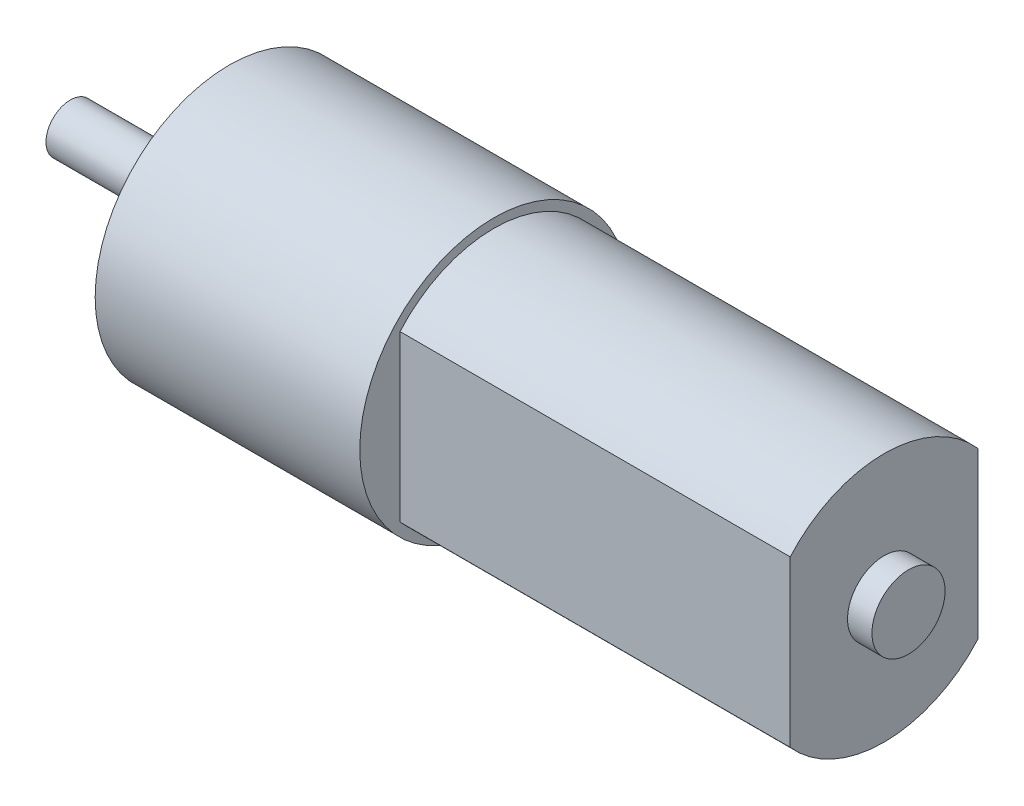
SolidWorks part; units mm, degrees
ref_plane "Plan de face" through (0, 0, 0) normal (0, 0, 1) x (1, 0, 0)
ref_plane "Plan de dessus" through (0, 0, 0) normal (0, 1, 0) x (1, 0, 0)
ref_plane "Plan de droite" through (0, 0, 0) normal (1, 0, 0) x (0, 0, -1)
sketch "Esquisse1" plane through (0, 0, 0) normal (0, 0, 1) x (1, 0, 0)
  line L0 (38.7034, 0) -> (-58.2382, 0) construction
  line L1 (-13.0357, 0) -> (-13.0357, -2)
  line L2 (-13.0357, -2) -> (-3, -2)
  line L3 (-3, -2) -> (-3, -4)
  line L4 (-3, -4) -> (-2, -4)
  line L5 (-2, -4) -> (-2, -7)
  line L6 (-2, -7) -> (0, -7)
  line L7 (0, -7) -> (0, -11)
  line L8 (0, -11) -> (21.7, -11)
  line L9 (21.7, -11) -> (21.7, -10.25)
  line L10 (21.7, -10.25) -> (53.7, -10.25)
  line L11 (53.7, -10.25) -> (53.7, -3)
  line L12 (53.7, -3) -> (55.7, -3)
  line L13 (55.7, -3) -> (55.7, 0)
  line L14 (55.7, 0) -> (-13.0357, 0)
  point P16 (0, -9)
  dimension "D1" = 2
  dimension "D2" = 11.0357
  dimension "D3" = 2
  dimension "D4" = 21.7
  dimension "D5" = 32
  dimension "D6" = 3
  dimension "D7" = 2
  dimension "D8" = 10.25
  dimension "D9" = 11
  dimension "D10" = 7
  dimension "D11" = 4
  dimension "D12" = 1
revolve "Révolution1" add sketch "Esquisse1" angle 360 about L0
sketch "Esquisse2" plane through (53.7, 0, 0) normal (1, 0, 0) x (0, 0, -1)
  line L0 (0, 0) -> (0, -12.8806) construction
  line L1 (-7.7, 11.1958) -> (-7.7, -12.176)
  line L2 (7.7, -12.176) -> (7.7, 11.1958)
  line L3 (-7.7, 11.1958) -> (-16.0203, 11.1958)
  line L4 (-16.0203, 11.1958) -> (-16.0203, -12.176)
  line L5 (-16.0203, -12.176) -> (-7.7, -12.176)
  line L6 (7.7, -12.176) -> (15.6221, -12.176)
  line L7 (15.6221, -12.176) -> (15.6221, 11.1958)
  line L8 (15.6221, 11.1958) -> (7.7, 11.1958)
  dimension "D1" = 15.4
extrude "Enlèv. mat.-Extru.1" cut sketch "Esquisse2" against normal up to surface (32 mm away) up to face at (21.7, 0, -10.25)
sketch "Esquisse3" plane through (-2, 0, 0) normal (-1, 0, 0) x (0, 0, 1)
  line L0 (6.7922, 1.6931) -> (1.6931, 6.7922)
  line L1 (0, 0) -> (-12.3198, 12.3198) construction
  line L2 (-6.7922, -1.6931) -> (-1.6931, -6.7922)
  line L3 (0, 15.4295) -> (0, 0) construction
  circle A0 centre (0, 0) radius 7 construction
  circle A1 centre (0, 0) radius 7 construction
  arc A2 (-6.7922, -1.6931) -> (-1.6931, -6.7922) centre (0, 0) ccw
  arc A3 (1.6931, 6.7922) -> (6.7922, 1.6931) centre (0, 0) cw
extrude "Enlèv. mat.-Extru.2" cut sketch "Esquisse3" against normal up to surface (2 mm away) up to face at (0, 0, -11)
sketch "Esquisse4" plane through (0, 0, 0) normal (-1, 0, 0) x (0, 0, 1)
  line L0 (-10.1299, 0) -> (9.83, 0) construction
  line L1 (0, -9.9871) -> (0, 10.1554) construction
  circle A0 centre (0, 0) radius 9 construction
  circle A1 centre (0, 9) radius 1
  circle A2 centre (-9, 0) radius 1
  circle A3 centre (0, -9) radius 1
  circle A4 centre (9, 0) radius 1
  dimension "D1" = 18
  dimension "D2" = 2
extrude "Enlèv. mat.-Extru.3" cut sketch "Esquisse4" against normal blind 4
